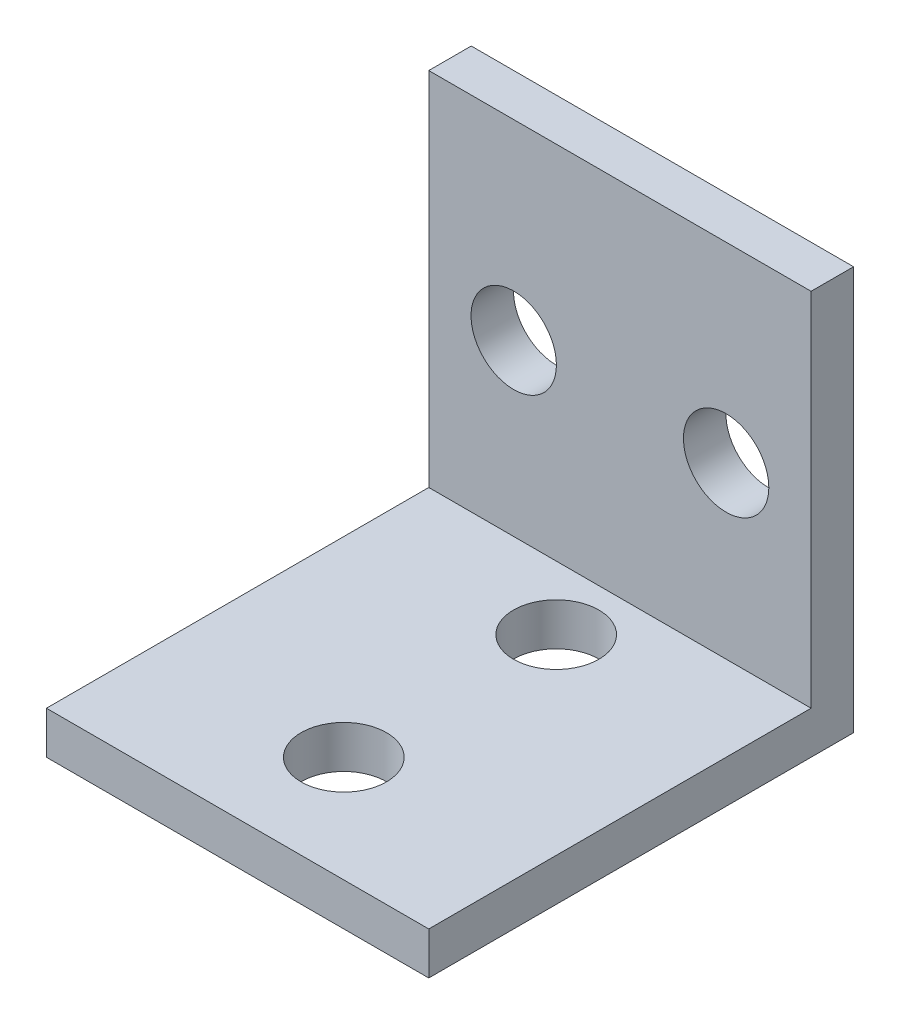
SolidWorks part; units mm, degrees
material "6061-T6 (SS)"
ref_plane "Front Plane" through (0, 0, 0) normal (0, 0, 1) x (1, 0, 0)
ref_plane "Top Plane" through (0, 0, 0) normal (0, 1, 0) x (1, 0, 0)
ref_plane "Right Plane" through (0, 0, 0) normal (1, 0, 0) x (0, 0, -1)
sketch "Sketch1" plane through (0, 0, 0) normal (0, 1, 0) x (1, 0, 0)
  line L1 (0, 0) -> (22.86, 0)
  line L2 (0, 0) -> (0, 25.4)
  line L3 (0, 25.4) -> (22.86, 25.4)
  line L4 (22.86, 0) -> (22.86, 25.4)
  dimension "D1" = 25.4
  dimension "D2" = 22.86
extrude "Boss-Extrude1" add sketch "Sketch1" along normal blind 24.13
sketch "Sketch2" plane through (22.86, 0, 0) normal (1, 0, 0) x (0, 0, -1)
  line L0 (0, 24.13) -> (25.4, 24.13) construction
  line L1 (22.86, 24.13) -> (0, 24.13)
  line L2 (22.86, 24.13) -> (22.86, 2.54)
  line L3 (22.86, 2.54) -> (0, 2.54)
  line L4 (0, 24.13) -> (0, 2.54)
  line L5 (0, 24.13) -> (0, 0) construction
  line L6 (25.4, 24.13) -> (25.4, 0) construction
  line L7 (0, 0) -> (25.4, 0) construction
  dimension "D1" = 2.54
  dimension "D2" = 2.54
extrude "Cut-Extrude1" cut sketch "Sketch2" against normal through all
sketch "Sketch3" plane through (0, 2.54, 0) normal (0, 1, 0) x (1, 0, 0)
  line L0 (0, 0) -> (22.86, 0) construction
  line L1 (0, 0) -> (0, 22.86) construction
  circle A0 centre (11.43, 6.35) radius 2.5527
  circle A1 centre (11.43, 19.05) radius 2.5527
  dimension "D1" = 5.1054
  dimension "D2" = 5.1054
  dimension "D3" = 12.7
  dimension "D4" = 6.35
  dimension "D5" = 11.43
  dimension "D6" = 11.43
extrude "Cut-Extrude2" cut sketch "Sketch3" against normal through all
sketch "Sketch4" plane through (0, 0, -22.86) normal (0, 0, 1) x (1, 0, 0)
  line L0 (0, 24.13) -> (22.86, 24.13) construction
  line L1 (0, 2.54) -> (0, 24.13) construction
  circle A0 centre (17.78, 12.7) radius 2.5527
  circle A1 centre (5.08, 12.7) radius 2.5527
  dimension "D1" = 5.1054
  dimension "D2" = 5.1054
  dimension "D3" = 11.43
  dimension "D4" = 5.08
  dimension "D5" = 11.43
  dimension "D6" = 12.7
extrude "Cut-Extrude3" cut sketch "Sketch4" against normal through all
